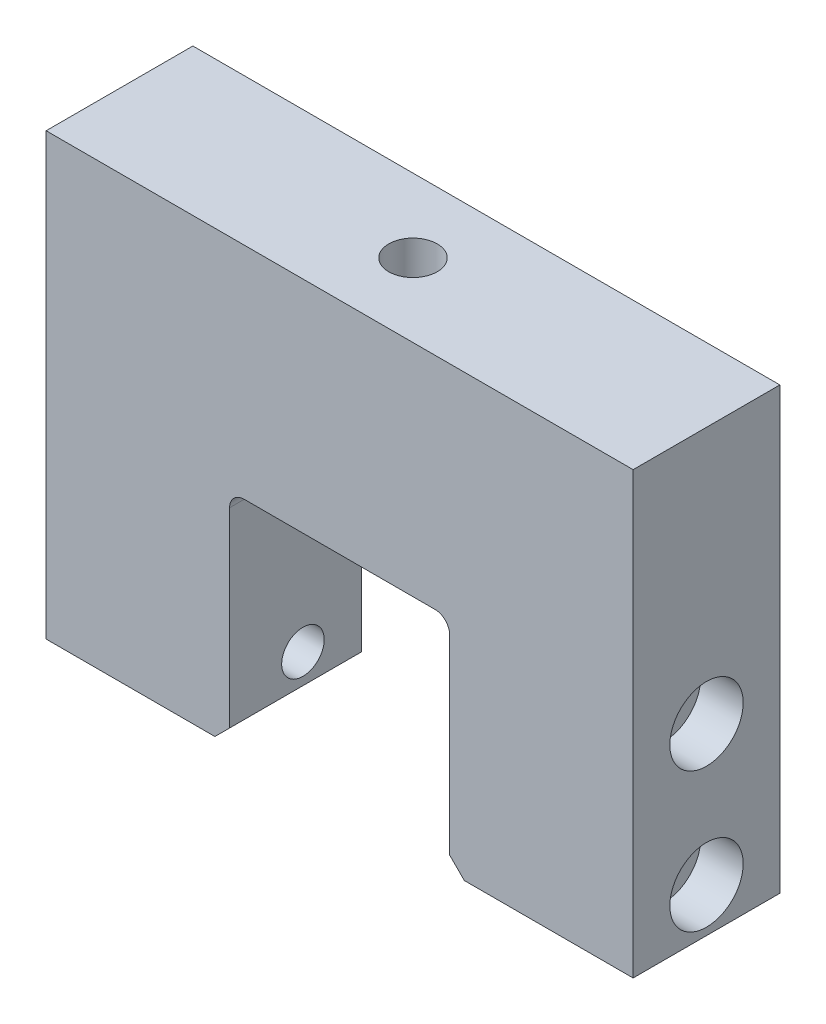
SolidWorks part; units mm, degrees
material "6061 Alloy"
ref_plane "Front Plane" through (0, 0, 0) normal (0, 0, 1) x (1, 0, 0)
ref_plane "Top Plane" through (0, 0, 0) normal (0, 1, 0) x (1, 0, 0)
ref_plane "Right Plane" through (0, 0, 0) normal (1, 0, 0) x (0, 0, -1)
sketch "Sketch1" plane through (0, 0, 0) normal (0, 0, 1) x (1, 0, 0)
  line L1 (20, 15) -> (-20, 15)
  line L2 (20, 15) -> (20, -15)
  line L3 (20, -15) -> (-20, -15)
  line L4 (-20, 15) -> (-20, -15)
  line L5 (20, 15) -> (-20, -15) construction
  line L6 (20, -15) -> (-20, 15) construction
  dimension "D1" = 30
  dimension "D2" = 40
extrude "Boss-Extrude1" add sketch "Sketch1" along normal blind 10
sketch "Sketch2" plane through (0, 0, 10) normal (0, 0, 1) x (1, 0, 0)
  line L0 (-20, -15) -> (20, -15) construction
  line L1 (-7.5, 0) -> (7.5, 0)
  line L2 (-7.5, 0) -> (-7.5, -15)
  line L3 (-7.5, -15) -> (7.5, -15)
  line L4 (7.5, 0) -> (7.5, -15)
  line L5 (-7.5, 0) -> (7.5, -15) construction
  line L6 (-7.5, -15) -> (7.5, 0) construction
  point P0 (0, -7.5)
  dimension "D1" = 15
extrude "Cut-Extrude1" cut sketch "Sketch2" against normal through all
hole_wizard "CBORE for M2.5 Slotted cheese head screws2" positions "Sketch3" profile "Sketch6" counterbore size "M2.5" standard "GB"
sketch "Sketch3" plane through (-20, 0, 0) normal (-1, 0, 0) x (0, 0, 1)
  line L0 (10, -15) -> (0, -15) construction
  line L1 (0, 0) -> (10, 0) construction
  line L2 (5, 15) -> (5, -15) construction
  line L3 (10, 15) -> (0, 15) construction
  point P0 (5, -2.5)
  point P2 (5, -12)
  dimension "D1" = 3
  dimension "D2" = 2.5
sketch "Sketch6" plane through (-20, -2.5, 5) normal (0, 1, 0) x (0, 0, 1)
  line L0 (0, 0) -> (0, 12.5)
  line L1 (0, 12.5) -> (1.45, 12.5)
  line L3 (1.45, 12.5) -> (1.45, 2.9)
  line L4 (1.45, 2.9) -> (2.5, 2.9)
  line L5 (2.5, 2.9) -> (2.5, 0)
  line L7 (2.5, 0) -> (0, 0)
  line L11 (0, -6.35) -> (0, 107.95) construction
  dimension "Thru Hole Dia." = 2.9
  dimension "Thru Hole Depth" = 12.5
  dimension "C'Bore Dia." = 5
  dimension "C'Bore Depth" = 2.9
mirror "Mirror1" about plane through (0, 0, 0) normal (1, 0, 0) of "CBORE for M2.5 Slotted cheese head screws2"
hole_wizard "M4 Tapped Hole1" positions "Sketch7" profile "Sketch8" tap size "M4" standard "GB"
sketch "Sketch7" plane through (0, 0, 0) normal (0, 0, -1) x (-1, 0, 0)
  line L0 (0, 5.5) -> (0, -5.5) construction
  line L1 (-7.5, -15) -> (-20, -15) construction
  line L2 (-20, 15) -> (20, 15) construction
  line L3 (-13.75, -15) -> (-13.75, 15) construction
  point P0 (-13.75, -7)
  point P2 (-13.75, 11)
  point P10 (13.75, 11)
  point P11 (13.75, -7)
  dimension "D1" = 8
  dimension "D2" = 4
sketch "Sketch8" plane through (13.75, -7, 0) normal (1, 0, 0) x (0, 1, 0)
  line L0 (0, 0) -> (0, 5.9914)
  line L1 (0, 5.9914) -> (1.65, 5)
  line L2 (1.65, 5) -> (1.65, 0)
  line L5 (1.65, 0) -> (0, 0)
  line L10 (0, 5.9914) -> (-1.65, 5) construction
  line L11 (0, -6.35) -> (0, 107.95) construction
  dimension "Tap Drill Dia." = 3.3
  dimension "Tap Drill Depth" = 5
  dimension "Drill Angle" = 118
cosmetic thread "Hole Thread1" parameters "D1"=8, "D2"=4
cosmetic thread "Hole Thread2" parameters "D1"=8, "D2"=4
cosmetic thread "Hole Thread3" parameters "D1"=8, "D2"=4
cosmetic thread "Hole Thread4" parameters "D1"=8, "D2"=4
fillet "Fillet1" radius 1 2 edges at (7.5, 0, 5) (-7.5, 0, 5)
chamfer "Chamfer1" distance 1 angle 45 2 edges at (-7.5, -15, 5) (7.5, -15, 5)
chamfer "Chamfer2" distance 1 angle 45 5 edges at (7.5, -7.5, 0) (-7.5, -7.5, 0) (7.2071, -0.2929, 0) (-7.2071, -0.2929, 0) (0, 0, 0)
hole_wizard "M4 Tapped Hole2" positions "Sketch9" profile "Sketch10" tap size "M4" standard "GB" end condition through all
sketch "Sketch9" plane through (0, 15, 0) normal (0, 1, 0) x (1, 0, 0)
  line L0 (-20, -5) -> (20, -5) construction
  line L1 (-20, -10) -> (-20, 0) construction
  line L2 (20, -10) -> (20, 0) construction
  point P0 (0, -5)
cosmetic thread "Hole Thread5" parameters "D2"=4
sketch "Sketch10" plane through (0, 15, 5) normal (1, 0, 0) x (0, 0, 1)
  line L0 (0, 0) -> (0, 30)
  line L1 (0, 30) -> (1.65, 30)
  line L2 (1.65, 30) -> (1.65, 0)
  line L5 (1.65, 0) -> (0, 0)
  line L11 (0, -6.35) -> (0, 107.95) construction
  dimension "Thru Tap Drill Dia." = 3.3
  dimension "Thru Tap Drill Depth" = 30
